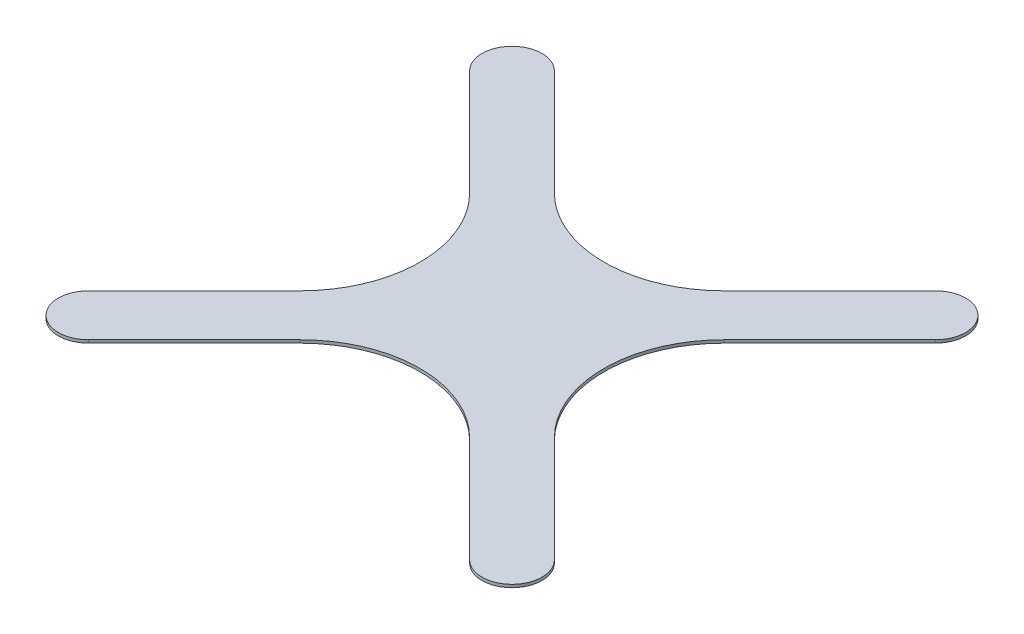
SolidWorks part; units mm, degrees
material "Thornel VCB-20 Carbon Cloth"
ref_plane "Front Plane" through (0, 0, 0) normal (0, 0, 1) x (1, 0, 0)
ref_plane "Top Plane" through (0, 0, 0) normal (0, 1, 0) x (1, 0, 0)
ref_plane "Right Plane" through (0, 0, 0) normal (1, 0, 0) x (0, 0, -1)
sketch "Sketch1" plane through (0, 0, 0) normal (0, 1, 0) x (1, 0, 0)
  line L13 (-96.8085, 144.2079) -> (-40.6819, 88.0813)
  line L15 (-96.8085, -57.8479) -> (-40.6819, -1.7213)
  line L16 (127.6979, 166.6585) -> (71.5713, 110.5319)
  line L17 (-74.3579, 166.6585) -> (-18.2313, 110.5319)
  line L18 (150.1485, 144.2079) -> (94.0219, 88.0813)
  line L19 (150.1485, -57.8479) -> (94.0219, -1.7213)
  line L20 (-74.3579, -80.2985) -> (-18.2313, -24.1719)
  line L21 (127.6979, -80.2985) -> (71.5713, -24.1719)
  arc A0 (-74.3579, 166.6585) -> (-96.8085, 144.2079) centre (-85.5832, 155.4332) ccw
  arc A2 (150.1485, 144.2079) -> (127.6979, 166.6585) centre (138.9232, 155.4332) ccw
  arc A3 (127.6979, -80.2985) -> (150.1485, -57.8479) centre (138.9232, -69.0732) ccw
  arc A4 (-96.8085, -57.8479) -> (-74.3579, -80.2985) centre (-85.5832, -69.0732) ccw
  arc A5 (-40.6819, -1.7213) -> (-40.6819, 88.0813) centre (-85.5832, 43.18) ccw
  arc A6 (71.5713, 110.5319) -> (-18.2313, 110.5319) centre (26.67, 155.4332) cw
  arc A7 (94.0219, 88.0813) -> (94.0219, -1.7213) centre (138.9232, 43.18) ccw
  arc A8 (-18.2313, -24.1719) -> (71.5713, -24.1719) centre (26.67, -69.0732) cw
extrude "Boss-Extrude1" add sketch "Sketch1" along normal blind 1.5748
